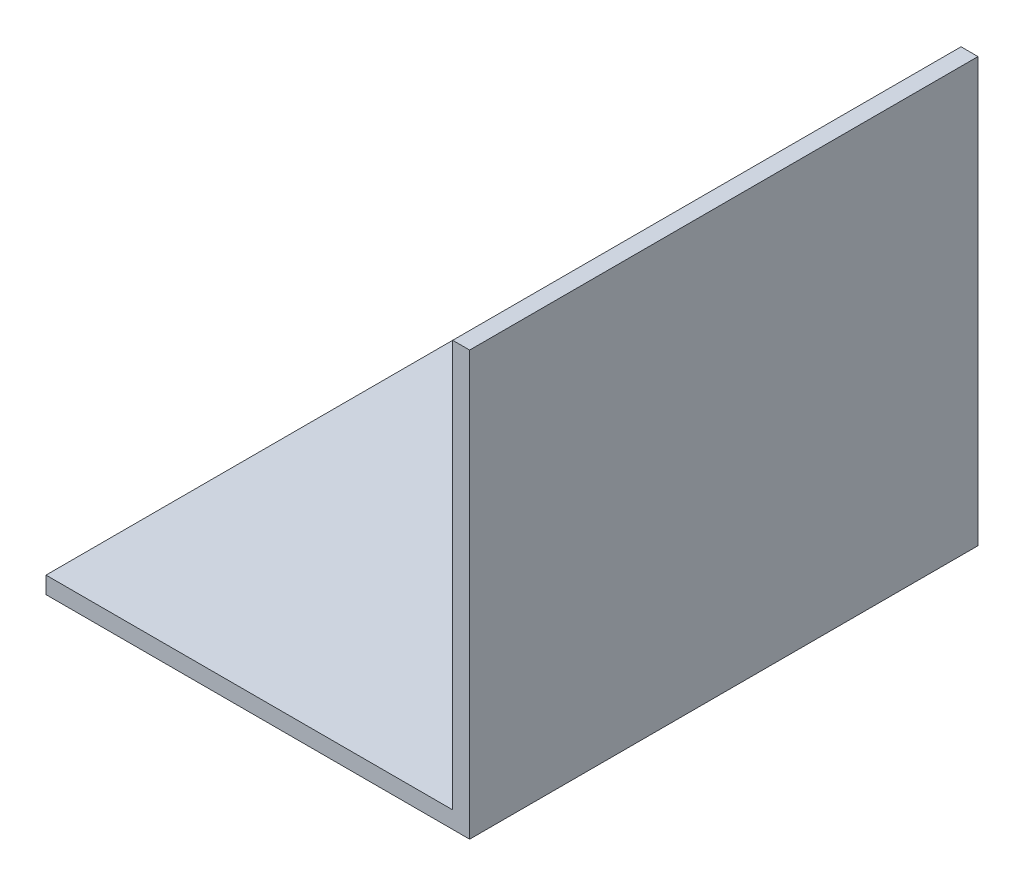
SolidWorks part; units mm, degrees
ref_plane "Front Plane" through (0, 0, 0) normal (0, 0, 1) x (1, 0, 0)
ref_plane "Top Plane" through (0, 0, 0) normal (0, 1, 0) x (1, 0, 0)
ref_plane "Right Plane" through (0, 0, 0) normal (1, 0, 0) x (0, 0, -1)
sketch "Sketch1" plane through (0, 0, 0) normal (0, 0, 1) x (1, 0, 0)
  line L0 (-31.1601, -13.564) -> (18.8399, -13.564)
  line L1 (18.8399, -13.564) -> (18.8399, 36.436)
  line L2 (18.8399, 36.436) -> (16.8399, 36.436)
  line L3 (16.8399, 36.436) -> (16.8399, -11.564)
  line L4 (16.8399, -11.564) -> (-31.1601, -11.564)
  line L5 (-31.1601, -11.564) -> (-31.1601, -13.564)
  dimension "D1" = 50
  dimension "D2" = 50
  dimension "D3" = 2
extrude "Boss-Extrude1" add sketch "Sketch1" along normal blind 60
